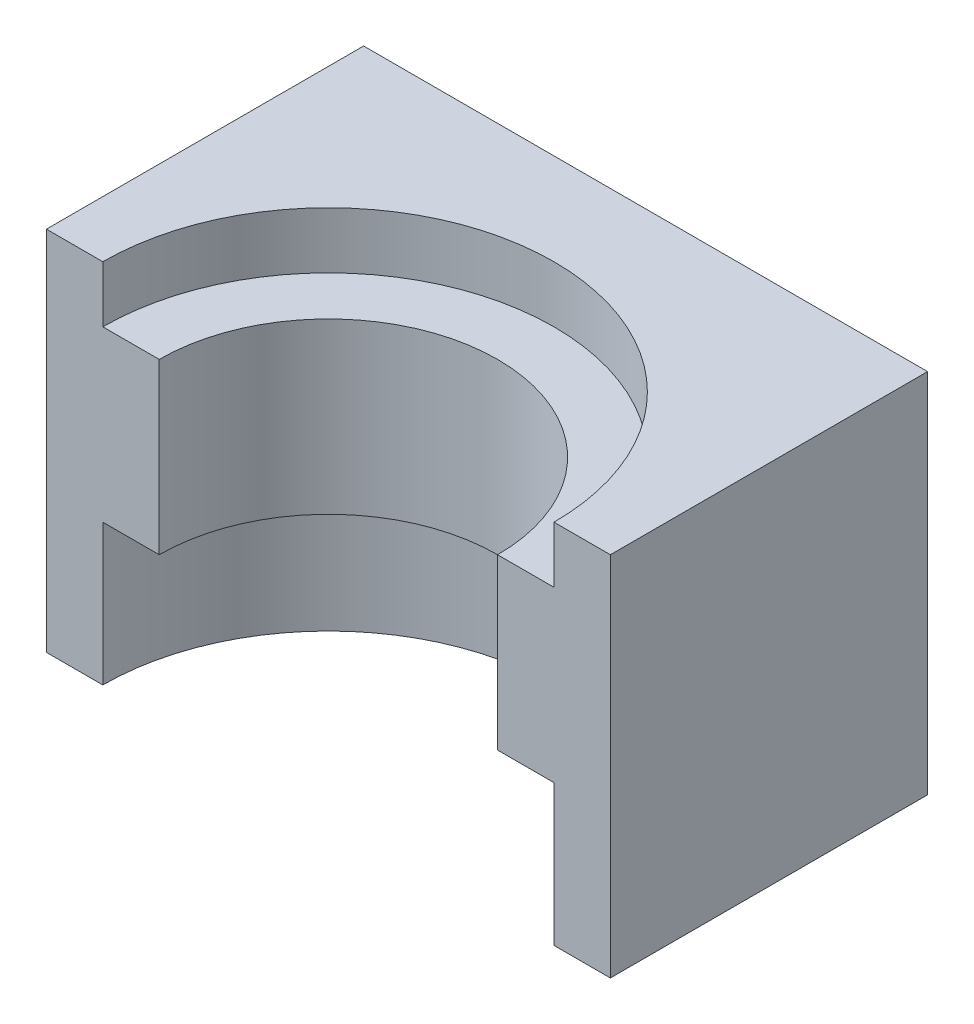
SolidWorks part; units mm, degrees
ref_plane "前视基准面" through (0, 0, 0) normal (0, 0, 1) x (1, 0, 0)
ref_plane "上视基准面" through (0, 0, 0) normal (0, 1, 0) x (1, 0, 0)
ref_plane "右视基准面" through (0, 0, 0) normal (1, 0, 0) x (0, 0, -1)
other "Configuration Table"
sketch "草图1" plane through (0, 0, 0) normal (0, 1, 0) x (1, 0, 0)
  line L0 (0, 8.75) -> (2, 8.75)
  line L2 (0, 8.75) -> (0, 20)
  line L3 (0, 20) -> (20, 20)
  line L4 (20, 8.75) -> (20, 20)
  line L5 (18, 8.75) -> (20, 8.75)
  arc A0 (18, 8.75) -> (2, 8.75) centre (10, 8.75) ccw
  point P10 (15.2903, 20)
  dimension "D3" = 16
  dimension "D1" = 20
  dimension "D2" = 11.25
  dimension "D4" = 10
  dimension "D5" = 11.25
extrude "凸台-拉伸1" add sketch "草图1" along normal blind 5
sketch "草图2" plane through (0, 5, 0) normal (0, 1, 0) x (1, 0, 0)
  line L0 (16, 8.75) -> (20, 8.75)
  line L1 (0, 20) -> (20, 20)
  line L2 (0, 20) -> (0, 8.75)
  line L3 (0, 8.75) -> (4, 8.75)
  line L4 (20, 20) -> (20, 8.75)
  arc A0 (16, 8.75) -> (4, 8.75) centre (10, 8.75) ccw
  dimension "D1" = 12
extrude "凸台-拉伸2" add sketch "草图2" along normal blind 6
sketch "草图3" plane through (0, 11, 0) normal (0, 1, 0) x (1, 0, 0)
  line L0 (18, 8.75) -> (20, 8.75)
  line L1 (0, 20) -> (20, 20)
  line L2 (0, 20) -> (0, 8.75)
  line L3 (0, 8.75) -> (2, 8.75)
  line L4 (20, 20) -> (20, 8.75)
  arc A0 (18, 8.75) -> (2, 8.75) centre (10, 8.75) ccw
  dimension "D1" = 16
extrude "凸台-拉伸3" add sketch "草图3" along normal blind 2
equation "\"D2@草图1\"=22.5/2"
equation "\"D5@草图1\"=\"D2@草图1\""
